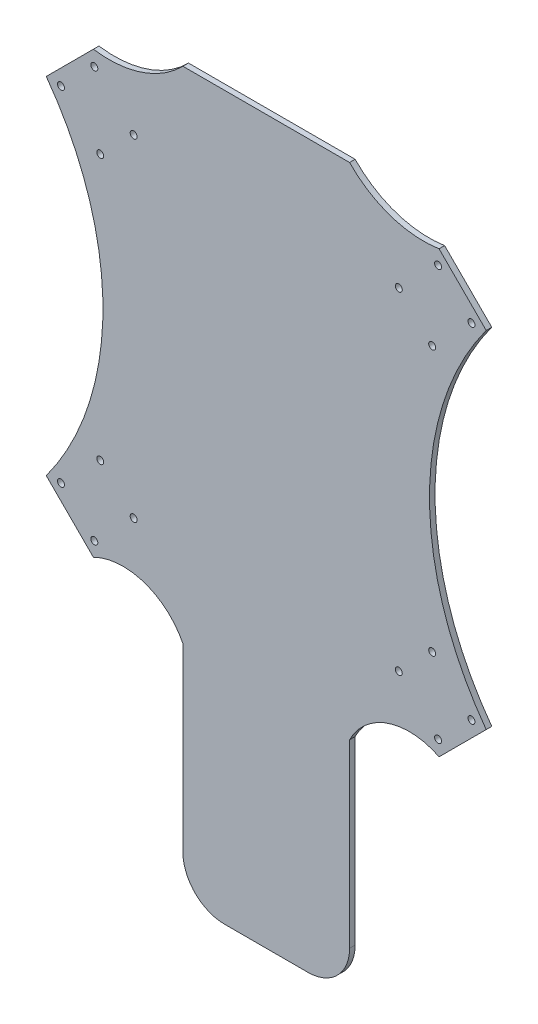
SolidWorks part; units mm, degrees
ref_plane "Front Plane" through (0, 0, 0) normal (0, 0, 1) x (1, 0, 0)
ref_plane "Top Plane" through (0, 0, 0) normal (0, 1, 0) x (1, 0, 0)
ref_plane "Right Plane" through (0, 0, 0) normal (1, 0, 0) x (0, 0, -1)
sketch "Sketch2" plane through (0, 0, 0) normal (0, 0, 1) x (1, 0, 0)
  line L0 (0, 0) -> (0, 50000) construction
  line L1 (0, 0) -> (35355.3391, 35355.3391) construction
  line L2 (0, 0) -> (35355.3391, -35355.3391) construction
  line L3 (-79.196, 62.2254) -> (-62.2254, 79.196)
  line L4 (0, 0) -> (-50000, 0) construction
  line L5 (-79.196, -62.2254) -> (-62.2254, -79.196)
  line L6 (30, 90) -> (-30, 90)
  line L7 (30, -90) -> (30, -155)
  line L8 (79.196, -62.2254) -> (62.2254, -79.196)
  line L9 (-30, -90) -> (-30, -155)
  line L10 (-15, -170) -> (15, -170)
  line L11 (79.196, 62.2254) -> (62.2254, 79.196)
  line L12 (-30, -90) -> (30, -170) construction
  line L13 (-30, -170) -> (30, -90) construction
  arc A0 (-79.196, 62.2254) -> (-79.196, -62.2254) centre (-163.8225, 0) cw
  arc A1 (-62.2254, 79.196) -> (-30, 90) centre (-56.6326, 115.976) ccw
  arc A2 (-62.2254, -79.196) -> (-30, -90) centre (-51.5147, -100.7107) cw
  arc A3 (15, -170) -> (30, -155) centre (15, -155) ccw
  arc A4 (-15, -170) -> (-30, -155) centre (-15, -155) cw
  arc A5 (62.2254, -79.196) -> (30, -90) centre (51.5147, -100.7107) ccw
  arc A6 (79.196, 62.2254) -> (79.196, -62.2254) centre (163.8225, 0) ccw
  arc A7 (62.2254, 79.196) -> (30, 90) centre (56.6326, 115.976) cw
  point P16 (-70.7107, 70.7107)
  point P24 (0, -130)
  point P32 (0, -170)
  point P45 (0, 90)
  dimension "D1" = 170
  dimension "D2" = 45
  dimension "D3" = 45
  dimension "D5" = 30
  dimension "D6" = 60
extrude "Boss-Extrude1" add sketch "Sketch2" along normal blind 2
sketch "Sketch3" plane through (0, 0, 2) normal (0, 0, 1) x (1, 0, 0)
  line L0 (-70.7107, 70.7107) -> (35284.6284, -35284.6284) construction
  line L1 (-79.196, 62.2254) -> (-62.2254, 79.196) construction
  line L2 (0, 90) -> (0, 50090) construction
  line L3 (30, 90) -> (-30, 90) construction
  line L4 (70.7107, 70.7107) -> (35426.0497, 35426.0497) construction
  line L5 (79.196, 62.2254) -> (62.2254, 79.196) construction
  line L6 (0, 0) -> (50000, 0) construction
  circle A0 centre (-73.8927, 61.8718) radius 1.25
  circle A1 centre (-59.7505, 47.7297) radius 1.25
  circle A2 centre (-61.8718, 73.8927) radius 1.25
  circle A3 centre (-47.7297, 59.7505) radius 1.25
  circle A4 centre (59.7505, 47.7297) radius 1.25
  circle A5 centre (73.8927, 61.8718) radius 1.25
  circle A6 centre (61.8718, 73.8927) radius 1.25
  circle A7 centre (47.7297, 59.7505) radius 1.25
  circle A8 centre (-59.7505, -47.7297) radius 1.25
  circle A9 centre (-47.7297, -59.7505) radius 1.25
  circle A10 centre (-61.8718, -73.8927) radius 1.25
  circle A11 centre (-73.8927, -61.8718) radius 1.25
  circle A12 centre (59.7505, -47.7297) radius 1.25
  circle A13 centre (73.8927, -61.8718) radius 1.25
  circle A14 centre (61.8718, -73.8927) radius 1.25
  circle A15 centre (47.7297, -59.7505) radius 1.25
  point P6 (-70.7107, 70.7107)
  point P17 (0, 90)
  point P30 (70.7107, 70.7107)
  dimension "D1" = 8.5
  dimension "D3" = 8.5
  dimension "D2" = 4
  dimension "D4" = 20
extrude "Cut-Extrude1" cut sketch "Sketch3" against normal through all
